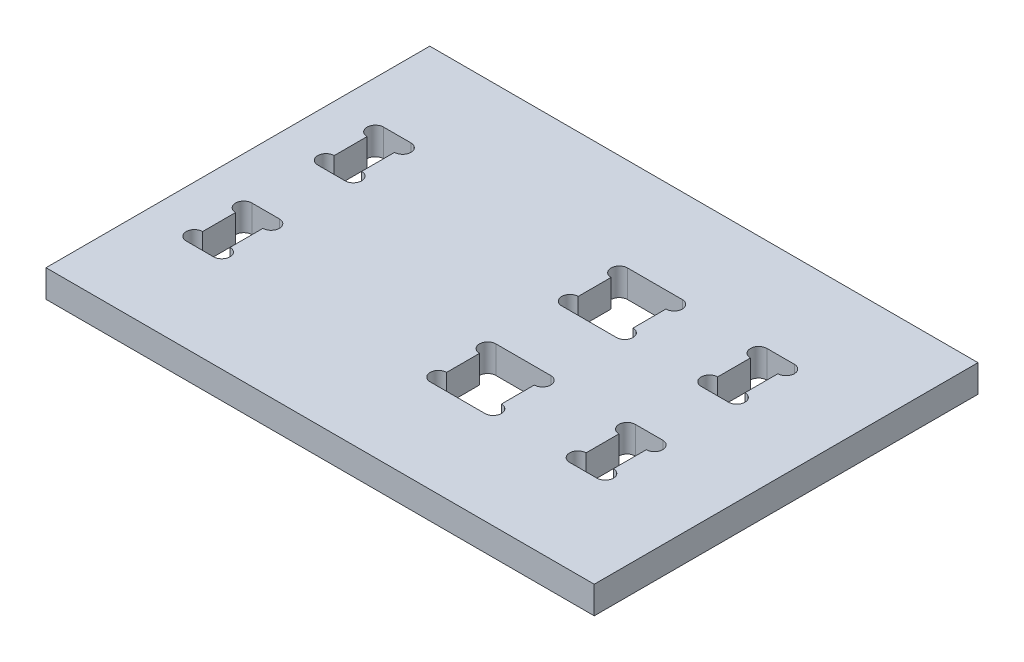
SolidWorks part; units mm, degrees
ref_plane "정면" through (0, 0, 0) normal (0, 0, 1) x (1, 0, 0)
ref_plane "윗면" through (0, 0, 0) normal (0, 1, 0) x (1, 0, 0)
ref_plane "우측면" through (0, 0, 0) normal (1, 0, 0) x (0, 0, -1)
sketch "스케치1" plane through (0, 0, 0) normal (0, 1, 0) x (1, 0, 0)
  line L1 (0, 0) -> (100, 0)
  line L2 (0, 0) -> (0, 70)
  line L3 (0, 70) -> (100, 70)
  line L4 (100, 0) -> (100, 70)
  dimension "D1" = 100
  dimension "D2" = 70
extrude "보스-돌출1" add sketch "스케치1" along normal blind 5
sketch "스케치2" plane through (0, 5, 0) normal (0, 1, 0) x (1, 0, 0)
  line L0 (53.07, 70) -> (53.07, 53) construction
  line L1 (53.07, 53) -> (63.07, 53)
  line L2 (53.07, 53) -> (53.07, 41)
  line L3 (53.07, 41) -> (63.07, 41)
  line L4 (63.07, 53) -> (63.07, 41)
  line L5 (53.07, 29) -> (63.07, 29)
  line L6 (53.07, 29) -> (53.07, 17)
  line L7 (53.07, 17) -> (63.07, 17)
  line L8 (63.07, 29) -> (63.07, 17)
  line L9 (100, 70) -> (0, 70) construction
  line L10 (53.07, 41) -> (53.07, 29) construction
  line L11 (53.07, 17) -> (53.07, 0) construction
  line L12 (0, 0) -> (100, 0) construction
  line L13 (63.07, 17) -> (78.5, 17) construction
  line L14 (78.5, 53) -> (83.5, 53)
  line L15 (78.5, 53) -> (78.5, 41)
  line L16 (78.5, 41) -> (83.5, 41)
  line L17 (83.5, 53) -> (83.5, 41)
  line L18 (78.5, 29) -> (83.5, 29)
  line L19 (78.5, 29) -> (78.5, 17)
  line L20 (78.5, 17) -> (83.5, 17)
  line L21 (83.5, 29) -> (83.5, 17)
  line L22 (83.5, 29) -> (83.5, 41) construction
  line L23 (78.5, 41) -> (78.5, 29) construction
  line L24 (78.5, 29) -> (63.07, 29) construction
  line L25 (63.07, 53) -> (78.5, 53) construction
  line L26 (78.5, 41) -> (63.07, 41) construction
  line L27 (63.07, 41) -> (62.9716, 40.9617) construction
  line L28 (53.07, 29) -> (13.57, 29) construction
  line L29 (8.57, 53) -> (13.57, 53)
  line L30 (8.57, 53) -> (8.57, 41)
  line L31 (8.57, 41) -> (13.57, 41)
  line L32 (13.57, 53) -> (13.57, 41)
  line L33 (13.57, 29) -> (8.57, 29)
  line L34 (13.57, 29) -> (13.57, 17)
  line L35 (13.57, 17) -> (8.57, 17)
  line L36 (8.57, 29) -> (8.57, 17)
  line L37 (13.57, 41) -> (13.57, 29) construction
  line L38 (13.57, 41) -> (53.07, 41) construction
  line L39 (53.07, 53) -> (13.57, 53) construction
  line L40 (8.57, 41) -> (8.57, 29) construction
  line L41 (13.57, 17) -> (53.07, 17) construction
  line L42 (100, 0) -> (100, 70) construction
  dimension "D1" = 10
  dimension "D2" = 12
  dimension "D3" = 12
  dimension "D4" = 12
  dimension "D5" = 15.43
  dimension "D6" = 5
  dimension "D7" = 39.5
  dimension "D8" = 5
  dimension "D9" = 16.5
extrude "컷-돌출1" cut sketch "스케치2" against normal blind 10
sketch "스케치3" plane through (0, 5, 0) normal (0, 1, 0) x (1, 0, 0)
  line L0 (8.57, 53) -> (8.57, 41) construction
  line L1 (13.57, 41) -> (13.57, 53) construction
  line L2 (8.57, 29) -> (8.57, 17) construction
  line L3 (13.57, 17) -> (13.57, 29) construction
  line L4 (63.07, 17) -> (63.07, 29) construction
  line L5 (53.07, 29) -> (53.07, 17) construction
  line L6 (78.5, 29) -> (78.5, 17) construction
  line L7 (83.5, 17) -> (83.5, 29) construction
  line L8 (78.5, 53) -> (78.5, 41) construction
  line L9 (83.5, 41) -> (83.5, 53) construction
  line L10 (63.07, 41) -> (63.07, 53) construction
  line L11 (53.07, 53) -> (53.07, 41) construction
  circle A0 centre (8.57, 51.5) radius 1.5
  circle A1 centre (13.57, 51.5) radius 1.5
  circle A2 centre (8.57, 42.5) radius 1.5
  circle A3 centre (13.57, 42.5) radius 1.5
  circle A4 centre (8.57, 27.5) radius 1.5
  circle A5 centre (13.57, 27.5) radius 1.5
  circle A6 centre (13.57, 18.5) radius 1.5
  circle A7 centre (8.57, 18.5) radius 1.5
  circle A8 centre (63.07, 18.5) radius 1.5
  circle A9 centre (53.07, 18.5) radius 1.5
  circle A10 centre (53.07, 27.5) radius 1.5
  circle A11 centre (63.07, 27.5) radius 1.5
  circle A12 centre (78.5, 27.5) radius 1.5
  circle A13 centre (83.5, 27.5) radius 1.5
  circle A14 centre (78.5, 18.5) radius 1.5
  circle A15 centre (83.5, 18.5) radius 1.5
  circle A16 centre (78.5, 42.5) radius 1.5
  circle A17 centre (83.5, 42.5) radius 1.5
  circle A18 centre (78.5, 51.5) radius 1.5
  circle A19 centre (83.5, 51.5) radius 1.5
  circle A20 centre (63.07, 51.5) radius 1.5
  circle A21 centre (53.07, 51.5) radius 1.5
  circle A22 centre (53.07, 42.5) radius 1.5
  circle A23 centre (63.07, 42.5) radius 1.5
  dimension "D1" = 3
extrude "컷-돌출2" cut sketch "스케치3" against normal blind 5
